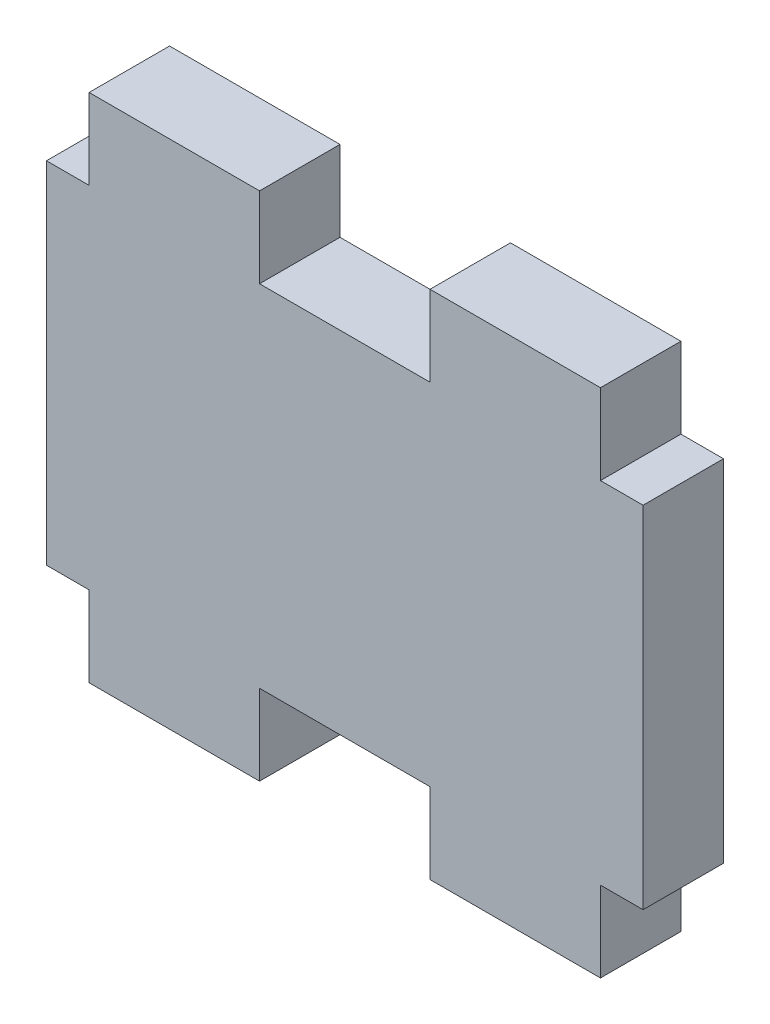
SolidWorks part; units mm, degrees
material "Acrylic (Medium-high impact)"
ref_plane "Front Plane" through (0, 0, 0) normal (0, 0, 1) x (1, 0, 0)
ref_plane "Top Plane" through (0, 0, 0) normal (0, 1, 0) x (1, 0, 0)
ref_plane "Right Plane" through (0, 0, 0) normal (1, 0, 0) x (0, 0, -1)
sketch "Sketch1" plane through (0, 0, 0) normal (0, 0, 1) x (1, 0, 0)
  line L0 (0, 6.5253) -> (22.225, 6.5253) construction
  line L1 (0, 0) -> (1.5875, 0)
  line L2 (0, 0) -> (0, 13.0505)
  line L3 (0, 13.0505) -> (1.5875, 13.0505)
  line L4 (22.225, 0) -> (22.225, 13.0505)
  line L5 (1.5875, 0) -> (1.5875, -2.9972)
  line L6 (1.5875, -2.9972) -> (7.9375, -2.9972)
  line L7 (7.9375, -2.9972) -> (7.9375, 0)
  line L8 (14.2875, 0) -> (14.2875, -2.9972)
  line L9 (14.2875, -2.9972) -> (20.6375, -2.9972)
  line L10 (20.6375, -2.9972) -> (20.6375, 0)
  line L11 (11.1125, 33.8328) -> (11.1125, 0) construction
  line L12 (20.6375, 16.0477) -> (20.6375, 13.0505)
  line L13 (14.2875, 16.0477) -> (20.6375, 16.0477)
  line L14 (14.2875, 13.0505) -> (14.2875, 16.0477)
  line L15 (7.9375, 16.0477) -> (7.9375, 13.0505)
  line L16 (1.5875, 16.0477) -> (7.9375, 16.0477)
  line L17 (1.5875, 13.0505) -> (1.5875, 16.0477)
  line L18 (7.9375, 13.0505) -> (14.2875, 13.0505)
  line L19 (20.6375, 13.0505) -> (22.225, 13.0505)
  line L20 (7.9375, 0) -> (14.2875, 0)
  line L21 (20.6375, 0) -> (22.225, 0)
  dimension "D1" = 13.0505
  dimension "D2" = 1.5875
  dimension "D3" = 6.35
  dimension "D4" = 2.9972
  dimension "D5" = 3.175
  dimension "D6" = 3.175
  dimension "D7" = 1.5875
extrude "Boss-Extrude1" add sketch "Sketch1" along normal blind 2.9972
